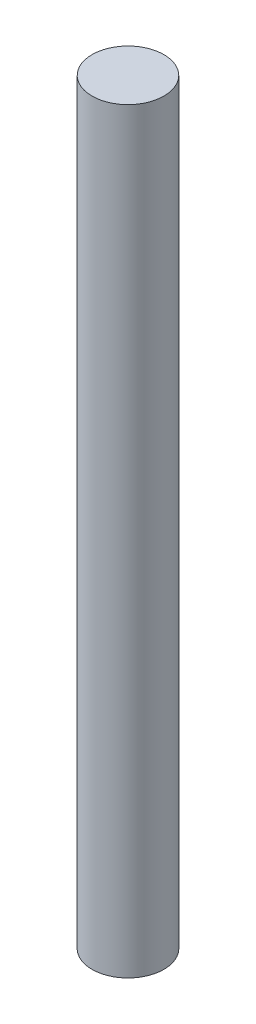
SolidWorks part; units mm, degrees
ref_plane "Front Plane" through (0, 0, 0) normal (0, 0, 1) x (1, 0, 0)
ref_plane "Top Plane" through (0, 0, 0) normal (0, 1, 0) x (1, 0, 0)
ref_plane "Right Plane" through (0, 0, 0) normal (1, 0, 0) x (0, 0, -1)
sketch "Sketch1" plane through (0, 0, 0) normal (0, 1, 0) x (1, 0, 0)
  circle A0 centre (0, 0) radius 4.75
  dimension "D1" = 9.5
extrude "Boss-Extrude1" add sketch "Sketch1" along normal blind 100
